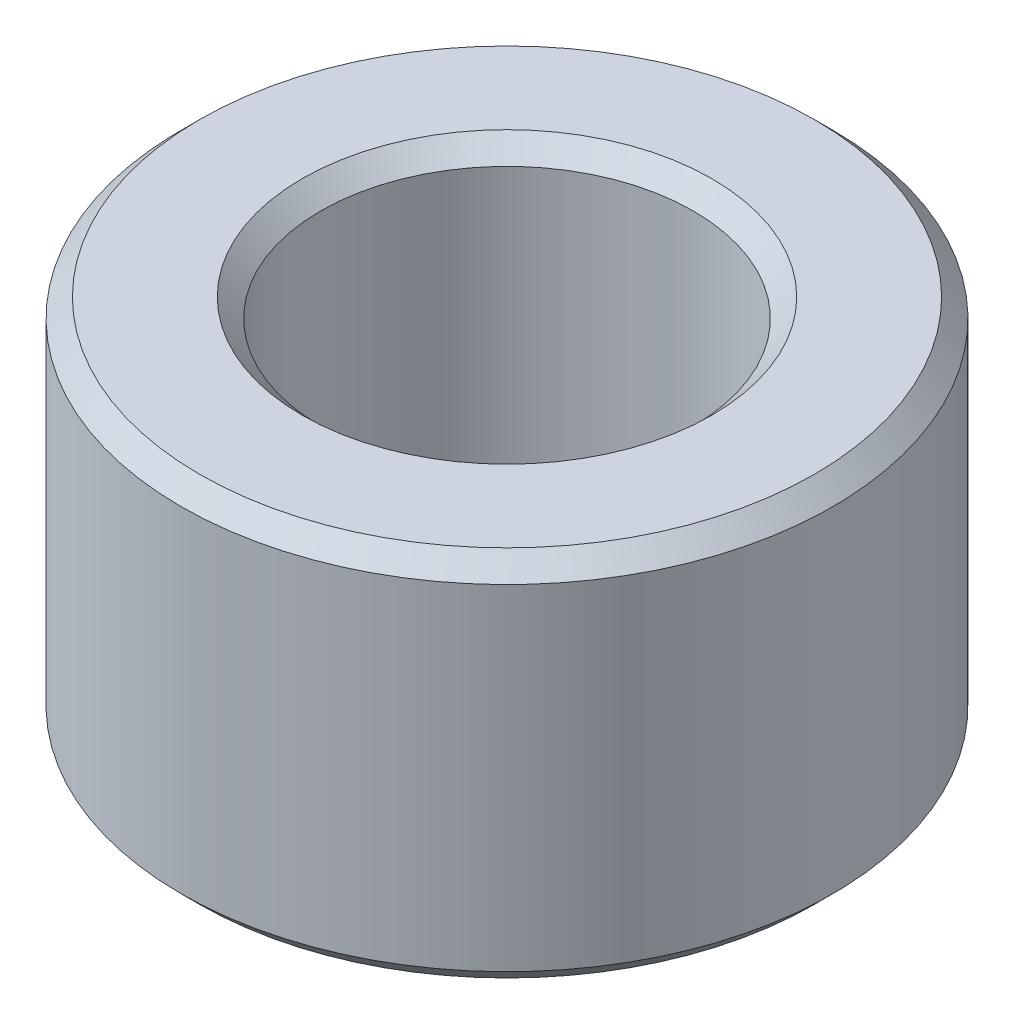
SolidWorks part; units mm, degrees
material "Stop 1060"
ref_plane "Płaszczyzna przednia" through (0, 0, 0) normal (0, 0, 1) x (1, 0, 0)
ref_plane "Płaszczyzna górna" through (0, 0, 0) normal (0, 1, 0) x (1, 0, 0)
ref_plane "Płaszczyzna prawa" through (0, 0, 0) normal (1, 0, 0) x (0, 0, -1)
sketch "Szkic1" plane through (0, 0, 0) normal (0, 1, 0) x (1, 0, 0)
  circle A0 centre (0, 0) radius 3.5
  circle A1 centre (0, 0) radius 2
  dimension "D1" = 7
  dimension "D2" = 4
extrude "Dodanie-wyciągnięcie1" add sketch "Szkic1" along normal blind 4
chamfer "Sfazowanie1" distance 0.2 angle 45 4 edges at (0, 0, 2) (0, 0, 3.5) (0, 4, 2) (0, 4, 3.5)
